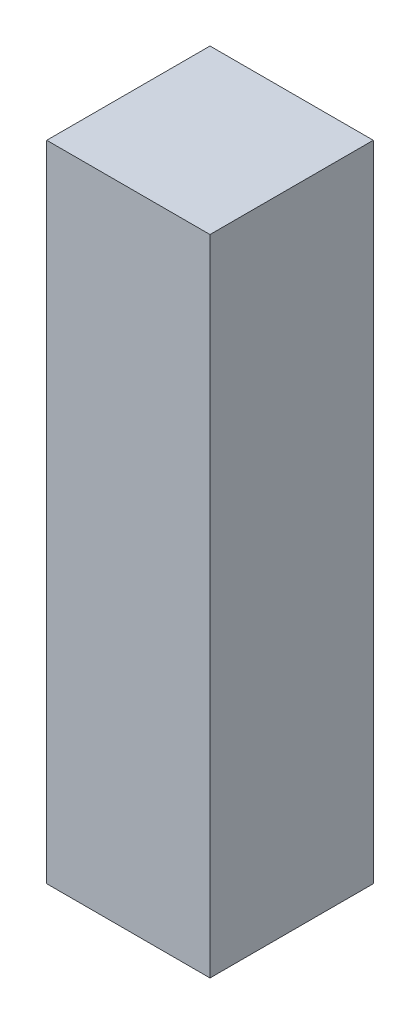
SolidWorks part; units mm, degrees
ref_plane "Front Plane" through (0, 0, 0) normal (0, 0, 1) x (1, 0, 0)
ref_plane "Top Plane" through (0, 0, 0) normal (0, 1, 0) x (1, 0, 0)
ref_plane "Right Plane" through (0, 0, 0) normal (1, 0, 0) x (0, 0, -1)
sketch "Sketch1" plane through (0, 0, 0) normal (0, 1, 0) x (1, 0, 0)
  line L1 (-8000, -7476.534) -> (8000, -7476.534)
  line L2 (-8000, -7476.534) -> (-8000, 8523.466)
  line L3 (-8000, 8523.466) -> (8000, 8523.466)
  line L4 (8000, -7476.534) -> (8000, 8523.466)
  line L5 (-8000, -7476.534) -> (8000, 8523.466) construction
  line L6 (-8000, 8523.466) -> (8000, -7476.534) construction
  dimension "D1" = 16000
  dimension "D2" = 16000
extrude "Boss-Extrude1" add sketch "Sketch1" along normal blind 63100
